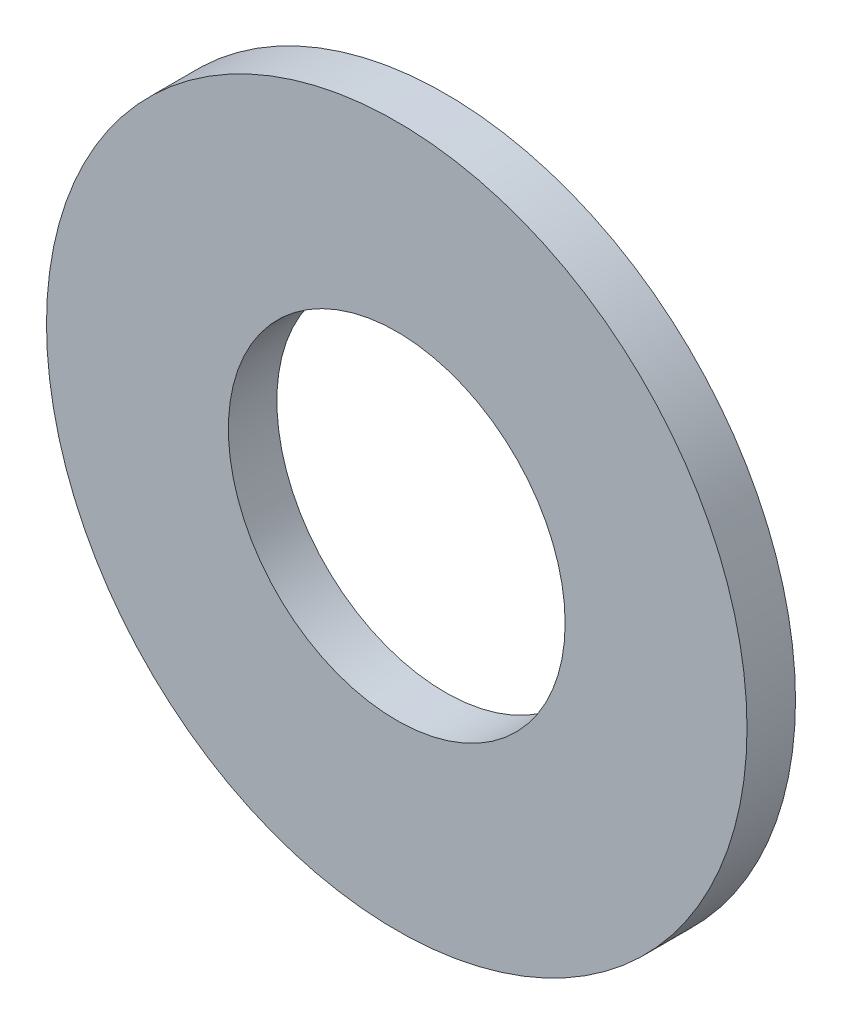
SolidWorks part; units mm, degrees
ref_plane "Front Plane" through (0, 0, 0) normal (0, 0, 1) x (1, 0, 0)
ref_plane "Top Plane" through (0, 0, 0) normal (0, 1, 0) x (1, 0, 0)
ref_plane "Right Plane" through (0, 0, 0) normal (1, 0, 0) x (0, 0, -1)
sketch "Sketch1" plane through (0, 0, 0) normal (0, 0, 1) x (1, 0, 0)
  circle A0 centre (0, 0) radius 26
  circle A1 centre (0, 0) radius 12.5
  dimension "D1" = 52
  dimension "D2" = 25
extrude "Boss-Extrude1" add sketch "Sketch1" along normal blind 3.6
